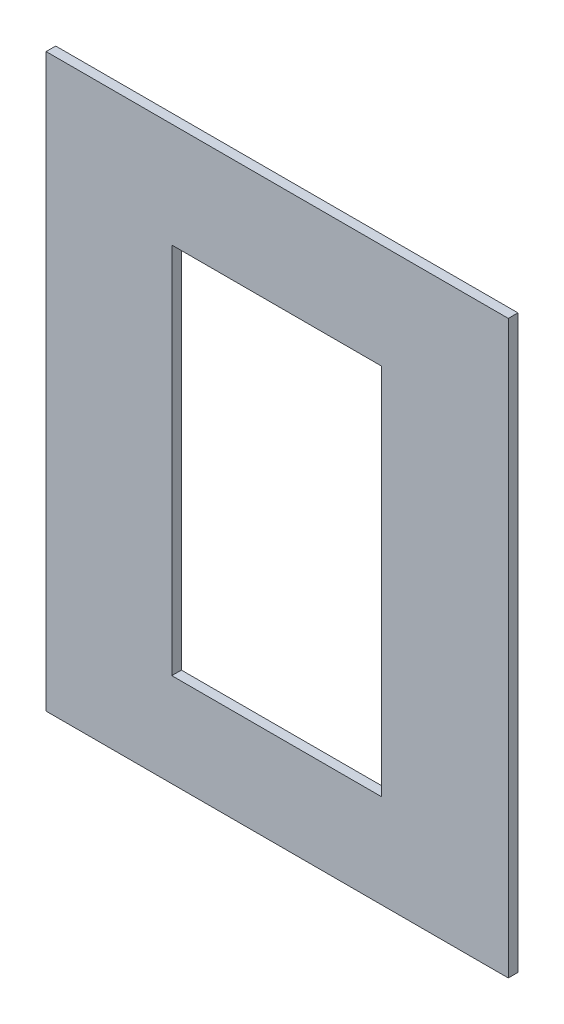
SolidWorks part; units mm, degrees
material "Plywood"
ref_plane "Front Plane" through (0, 0, 0) normal (0, 0, 1) x (1, 0, 0)
ref_plane "Top Plane" through (0, 0, 0) normal (0, 1, 0) x (1, 0, 0)
ref_plane "Right Plane" through (0, 0, 0) normal (1, 0, 0) x (0, 0, -1)
sketch "Sketch1" plane through (0, 0, 0) normal (0, 0, 1) x (1, 0, 0)
  line L1 (-438.9437, 542.5281) -> (438.9438, 542.5281)
  line L2 (-438.9437, 542.5281) -> (-438.9437, -542.5281)
  line L3 (-438.9437, -542.5281) -> (438.9438, -542.5281)
  line L4 (438.9438, 542.5281) -> (438.9438, -542.5281)
  line L5 (-438.9437, 542.5281) -> (438.9438, -542.5281) construction
  line L6 (-438.9437, -542.5281) -> (438.9438, 542.5281) construction
  point P0 (0, 0)
  dimension "D1" = 1085.0563
  dimension "D2" = 877.8875
extrude "Boss-Extrude1" add sketch "Sketch1" along normal blind 18.2562
sketch "Sketch2" plane through (0, 0, 18.2562) normal (0, 0, 1) x (1, 0, 0)
  line L0 (-438.9437, 0) -> (-200.1837, 0) construction
  line L1 (-200.1837, 343.6679) -> (198.3423, 343.6679)
  line L2 (-200.1837, 343.6679) -> (-200.1837, -364.7381)
  line L3 (-200.1837, -364.7381) -> (198.3423, -364.7381)
  line L4 (198.3423, 343.6679) -> (198.3423, -364.7381)
  line L5 (-438.9437, 542.5281) -> (-438.9437, -542.5281) construction
  line L6 (438.9438, 0) -> (198.3423, 0) construction
  line L7 (438.9438, -542.5281) -> (438.9438, 542.5281) construction
  line L8 (0, 542.5281) -> (-0.9207, 343.6679) construction
  line L9 (438.9438, 542.5281) -> (-438.9437, 542.5281) construction
  line L10 (0, -542.5281) -> (-0.9207, -364.7381) construction
  line L11 (-438.9437, -542.5281) -> (438.9438, -542.5281) construction
extrude "Cut-Extrude1" cut sketch "Sketch2" against normal blind 19.05
